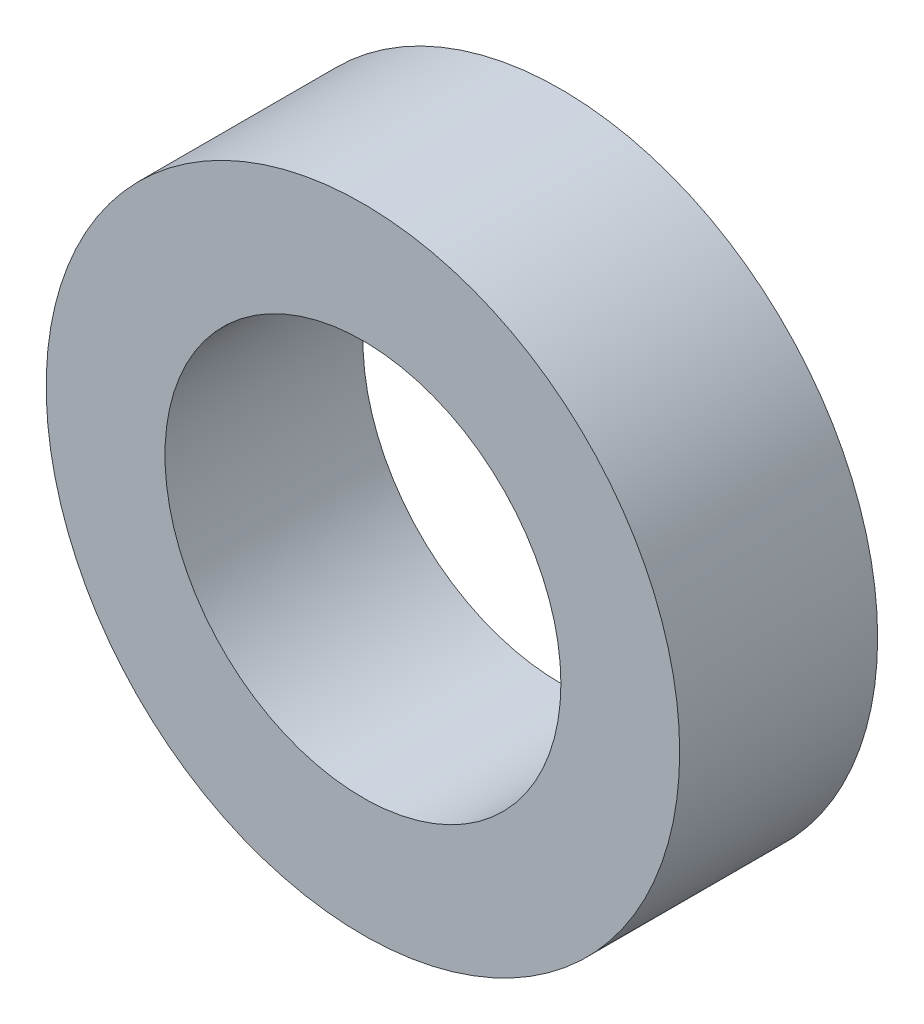
SolidWorks part; units mm, degrees
ref_plane "Front Plane" through (0, 0, 0) normal (0, 0, 1) x (1, 0, 0)
ref_plane "Top Plane" through (0, 0, 0) normal (0, 1, 0) x (1, 0, 0)
ref_plane "Right Plane" through (0, 0, 0) normal (1, 0, 0) x (0, 0, -1)
sketch "Sketch1" plane through (0, 0, 0) normal (0, 0, 1) x (1, 0, 0)
  circle A0 centre (0, 0) radius 2.5
  circle A1 centre (0, 0) radius 4
  dimension "D1" = 5
  dimension "D2" = 8
extrude "Boss-Extrude1" add sketch "Sketch1" along normal blind 2.5
